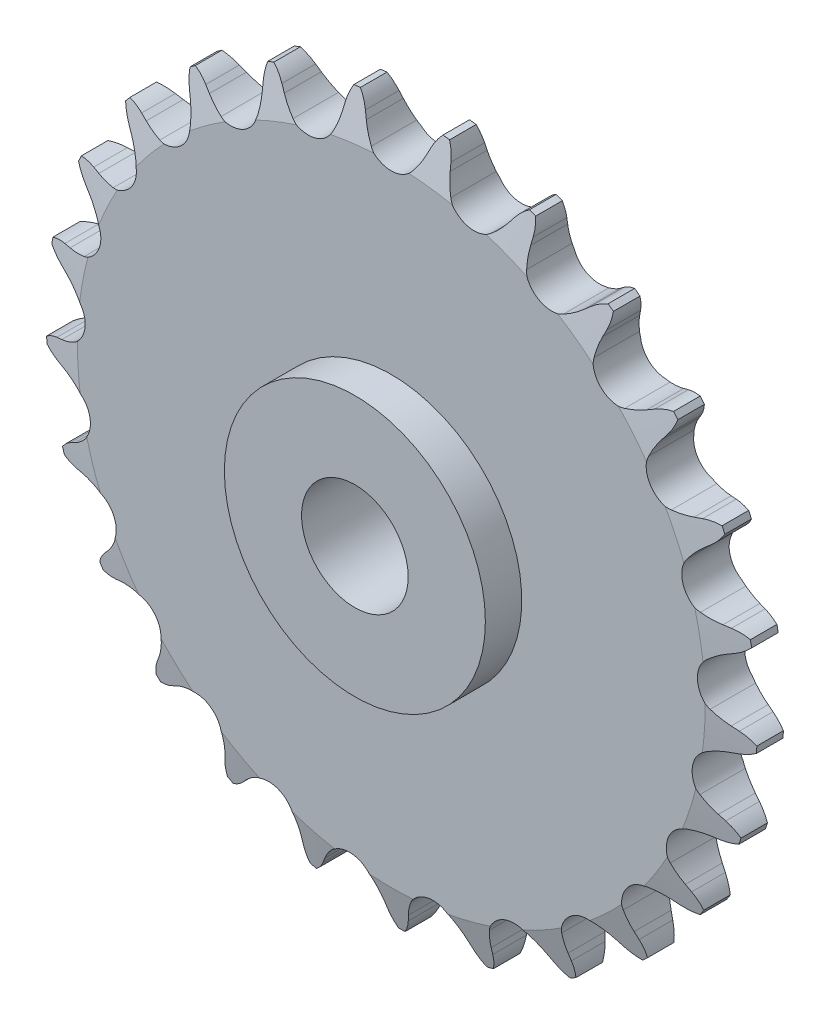
SolidWorks part; units mm, degrees
ref_plane "Front Plane" through (0, 0, 0) normal (0, 0, 1) x (1, 0, 0)
ref_plane "Top Plane" through (0, 0, 0) normal (0, 1, 0) x (1, 0, 0)
ref_plane "Right Plane" through (0, 0, 0) normal (1, 0, 0) x (0, 0, -1)
sketch "Sketch0" plane through (0, 0, 0) normal (0, 0, 1) x (1, 0, 0)
  line L0 (6.35, -50.2654) -> (0, 0) construction
  line L1 (0, 0) -> (18.651, -47.1071) construction
  line L2 (0, 0) -> (-6.35, -50.2654) construction
  line L3 (6.35, -50.2654) -> (18.651, -47.1071) construction
  line L4 (6.35, -50.2654) -> (-6.35, -50.2654) construction
  line L5 (11.415, -50.6347) -> (10.9111, -49.7196)
  line L6 (6.35, -50.2654) -> (0, -51.0676) construction
  line L7 (1.536, -51.8827) -> (1.7965, -50.871)
  line L8 (0, -50.2654) -> (0, -54.0754) construction
  line L9 (9.2126, -47.4426) -> (1.8359, -54.717) construction
  line L10 (0, 0) -> (0, -50.2654) construction
  line L11 (10.9111, -49.7196) -> (1.8359, -54.717) construction
  line L12 (0, -54.0754) -> (0, -54.687) construction
  line L13 (17.0962, -47.5063) -> (11.415, -50.6347) construction
  circle A0 centre (0, 0) radius 54.0754 construction
  circle A1 centre (0, 0) radius 50.6649 construction
  arc A2 (-5.3542, -56.7223) -> (19.2923, -53.6087) centre (0, 0) ccw
  circle A3 centre (0, 0) radius 54.687 construction
  circle A4 centre (6.35, -50.2654) radius 3.9624 construction
  arc A7 (9.2126, -47.4426) -> (2.8753, -48.2431) centre (6.35, -50.2654) ccw
  circle A8 centre (6.35, -50.2654) radius 4.0203 construction
  arc A9 (11.415, -50.6347) -> (19.2923, -53.6087) centre (17.0962, -47.5063) ccw
  arc A10 (10.9111, -49.7196) -> (9.2126, -47.4426) centre (1.8359, -54.717) ccw
  arc A11 (1.536, -51.8827) -> (-5.3542, -56.7223) centre (-4.7447, -50.2654) cw
  arc A12 (1.7965, -50.871) -> (2.8753, -48.2431) centre (11.8294, -53.4545) cw
  dimension "D1" = 4.0203
  dimension "R" = 4.0203
sketch "Sketch1" plane through (0, 0, 0) normal (1, 0, 0) x (0, 0, -1)
  line L0 (-3.6068, 0) -> (3.6068, 0)
  line L1 (-3.6068, 0) -> (-3.6068, 47.7254)
  line L2 (-3.6068, 47.7254) -> (-2.0193, 54.0754)
  line L3 (-2.0193, 54.0754) -> (2.0193, 54.0754)
  line L4 (2.0193, 54.0754) -> (3.6068, 47.7254)
  line L5 (3.6068, 47.7254) -> (3.6068, 0)
  line L7 (0, 54.0754) -> (0, 0) construction
  line L8 (-3.6068, 47.7254) -> (3.6068, 47.7254) construction
  line L9 (0, 54.0754) -> (0, -54.0754) construction
  line L10 (-3.6068, 47.7254) -> (-3.6068, 54.0754) construction
  line L11 (-3.6068, 54.0754) -> (-2.0193, 54.0754) construction
  line L12 (2.0193, 54.0754) -> (3.6068, 54.0754) construction
  line L13 (3.6068, 54.0754) -> (3.6068, 47.7254) construction
revolve "Revolve1" add sketch "Sketch1" angle 360 mid plane about L0
extrude "Cut-Extrude1" cut sketch "Sketch0" against normal through all and the other way through all
pattern_circular "CirPattern1" count 25 over 360 about axis through (0, 0, 0) along (0, 0, 1) of "Cut-Extrude1"
sketch "Sketch2" plane through (0, 0, 0) normal (0, 0, 1) x (1, 0, 0)
  circle A0 centre (0, 0) radius 8.1026 construction
  circle A1 centre (0, 0) radius 19.8438
  circle A2 centre (0, 0) radius 54.102 construction
  dimension "Bore" = 16.2052
  dimension "Hub Dia." = 39.6875
  dimension "OD" = 108.204
extrude "Boss-Extrude1" add sketch "Sketch2" along normal mid plane 18.288
sketch "Sketch3" plane through (0, 0, 0) normal (0, 0, 1) x (1, 0, 0)
  circle A0 centre (0, 0) radius 8.1026 construction
  circle A1 centre (0, 0) radius 8.1026
extrude "Cut-Extrude2" cut sketch "Sketch3" along normal through all and the other way through all
ref_plane "Plane1" through (0, 0, 0) normal (0, 0, 1) x (1, 0, 0)
equation "\"360/N@Sketch0\" = 360/\"Teeth@CirPattern1\""
equation "\"Ds@Sketch0\" = 1.005 * \"Dr@Sketch0\" + 0.003"
equation "\"R@Sketch0\" = 1/2 * \"Ds@Sketch0\""
equation "\"A@Sketch0\" = 35 +  ( 60 / \"Teeth@CirPattern1\" ) "
equation "\"B@Sketch0\" = 18 -  ( 56 / \"Teeth@CirPattern1\" )"
equation "\"ac@Sketch0\" = 0.8 * \"Dr@Sketch0\""
equation "\"ab@Sketch0\" = 1.4 * \"Dr@Sketch0\""
equation "\"J@Sketch0\" = 0.3 * \"Pitch@Sketch0\""
equation "\"h@Sketch1\" = \"Pitch@Sketch0\" / 2"
equation "\"g@Sketch1\" = \"h@Sketch1\" / 4"
